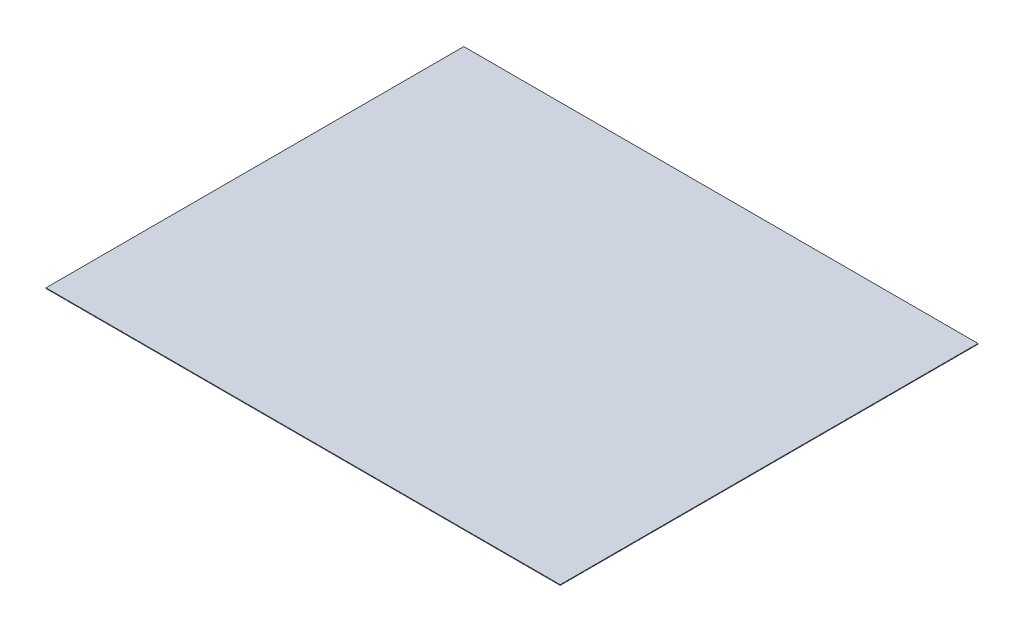
SolidWorks part; units mm, degrees
ref_plane "Front Plane" through (0, 0, 0) normal (0, 0, 1) x (1, 0, 0)
ref_plane "Top Plane" through (0, 0, 0) normal (0, 1, 0) x (1, 0, 0)
ref_plane "Right Plane" through (0, 0, 0) normal (1, 0, 0) x (0, 0, -1)
sketch "Sketch1" plane through (0, 0, 0) normal (0, 1, 0) x (1, 0, 0)
  line L1 (-800, -650) -> (800, -650)
  line L2 (-800, -650) -> (-800, 650)
  line L3 (-800, 650) -> (800, 650)
  line L4 (800, -650) -> (800, 650)
  line L5 (-800, -650) -> (800, 650) construction
  line L6 (-800, 650) -> (800, -650) construction
  point P0 (0, 0)
  dimension "D1" = 1600
  dimension "D2" = 1300
extrude "Boss-Extrude1" add sketch "Sketch1" along normal blind 2
